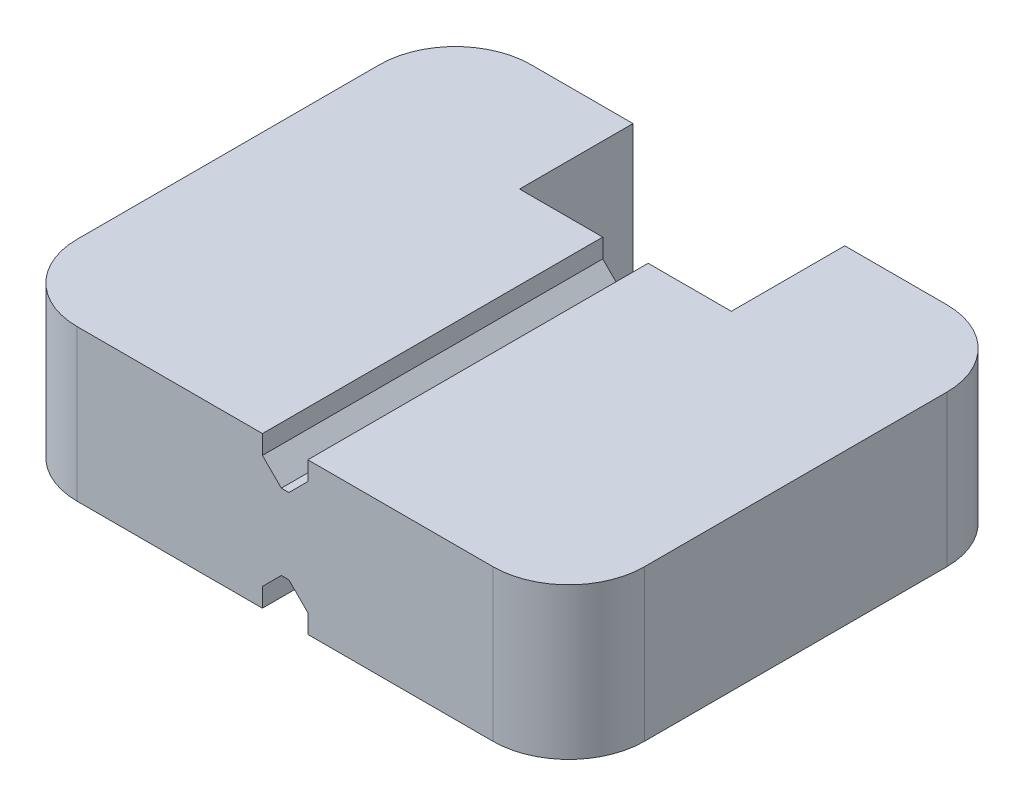
SolidWorks part; units mm, degrees
ref_plane "Plano frontal" through (0, 0, 0) normal (0, 0, 1) x (1, 0, 0)
ref_plane "Plano superior" through (0, 0, 0) normal (0, 1, 0) x (1, 0, 0)
ref_plane "Plano direito" through (0, 0, 0) normal (1, 0, 0) x (0, 0, -1)
sketch "Esboço1" plane through (0, 0, 0) normal (0, 1, 0) x (1, 0, 0)
  line L1 (-7.5, 6) -> (7.5, 6)
  line L2 (-7.5, 6) -> (-7.5, -6)
  line L3 (-7.5, -6) -> (7.5, -6)
  line L4 (7.5, 6) -> (7.5, -6)
  line L5 (-7.5, 6) -> (7.5, -6) construction
  line L6 (-7.5, -6) -> (7.5, 6) construction
  point P0 (0, 0)
  dimension "D1" = 12
  dimension "D2" = 15
extrude "Ressalto-extrusão1" add sketch "Esboço1" along normal blind 4
sketch "Esboço2" plane through (0, 4, 0) normal (0, 1, 0) x (1, 0, 0)
  line L0 (0, 11.1412) -> (0, -10.9606) construction
  line L1 (7.5, 6) -> (-7.5, 6) construction
  line L2 (-2.8, 9) -> (2.8, 9)
  line L3 (-2.8, 9) -> (-2.8, 3)
  line L4 (-2.8, 3) -> (2.8, 3)
  line L5 (2.8, 9) -> (2.8, 3)
  line L6 (-2.8, 9) -> (2.8, 3) construction
  line L7 (-2.8, 3) -> (2.8, 9) construction
  point P3 (0, 6)
  dimension "D1" = 6
  dimension "D2" = 5.6
extrude "Corte-extrusão1" cut sketch "Esboço2" against normal through all
sketch "Esboço3" plane through (0, 4, 0) normal (0, 1, 0) x (1, 0, 0)
  line L0 (0, 11.0118) -> (0, -10.7317) construction
  line L1 (-2.8, 3) -> (2.8, 3) construction
  line L2 (-0.6, -7) -> (0.6, -7)
  line L3 (-0.6, -7) -> (-0.6, 3)
  line L4 (-0.6, 3) -> (0.6, 3)
  line L5 (0.6, -7) -> (0.6, 3)
  line L6 (-0.6, -7) -> (0.6, 3) construction
  line L7 (-0.6, 3) -> (0.6, -7) construction
  point P3 (0, -2)
  dimension "D1" = 10
  dimension "D2" = 1.2
extrude "Corte-extrusão2" cut sketch "Esboço3" against normal blind 1
ref_plane "Plano1" through (0.6, 3, -3) normal (0, 0, -1) x (-1, 0, 0)
chamfer "Chanfro1" distance 0.5 angle 45 2 edges at (0.6, 3, 1.5) (-0.6, 3, 1.5)
fillet "Filete1" radius 2 1 edges at (7.5, 2, 6)
fillet "Filete2" radius 2 1 edges at (7.5, 2, -6)
fillet "Filete3" radius 2 1 edges at (-7.5, 2, 6)
fillet "Filete4" radius 2 1 edges at (-7.5, 2, -6)
sketch "Esboço4" plane through (0, 0, 0) normal (0, -1, 0) x (1, 0, 0)
  line L0 (0, 6.6028) -> (0, -5.0876) construction
  line L1 (-54.4, -3) -> (55.6, -3) construction
  line L2 (-0.6, 7) -> (0.6, 7)
  line L3 (-0.6, 7) -> (-0.6, -3)
  line L4 (-0.6, -3) -> (0.6, -3)
  line L5 (0.6, 7) -> (0.6, -3)
  line L6 (-0.6, 7) -> (0.6, -3) construction
  line L7 (-0.6, -3) -> (0.6, 7) construction
  point P3 (0, 2)
  dimension "D1" = 10
  dimension "D2" = 1.2
extrude "Corte-extrusão3" cut sketch "Esboço4" against normal blind 1
chamfer "Chanfro2" distance 0.5 angle 45 2 edges at (0.6, 1, 1.5) (-0.6, 1, 1.5)
